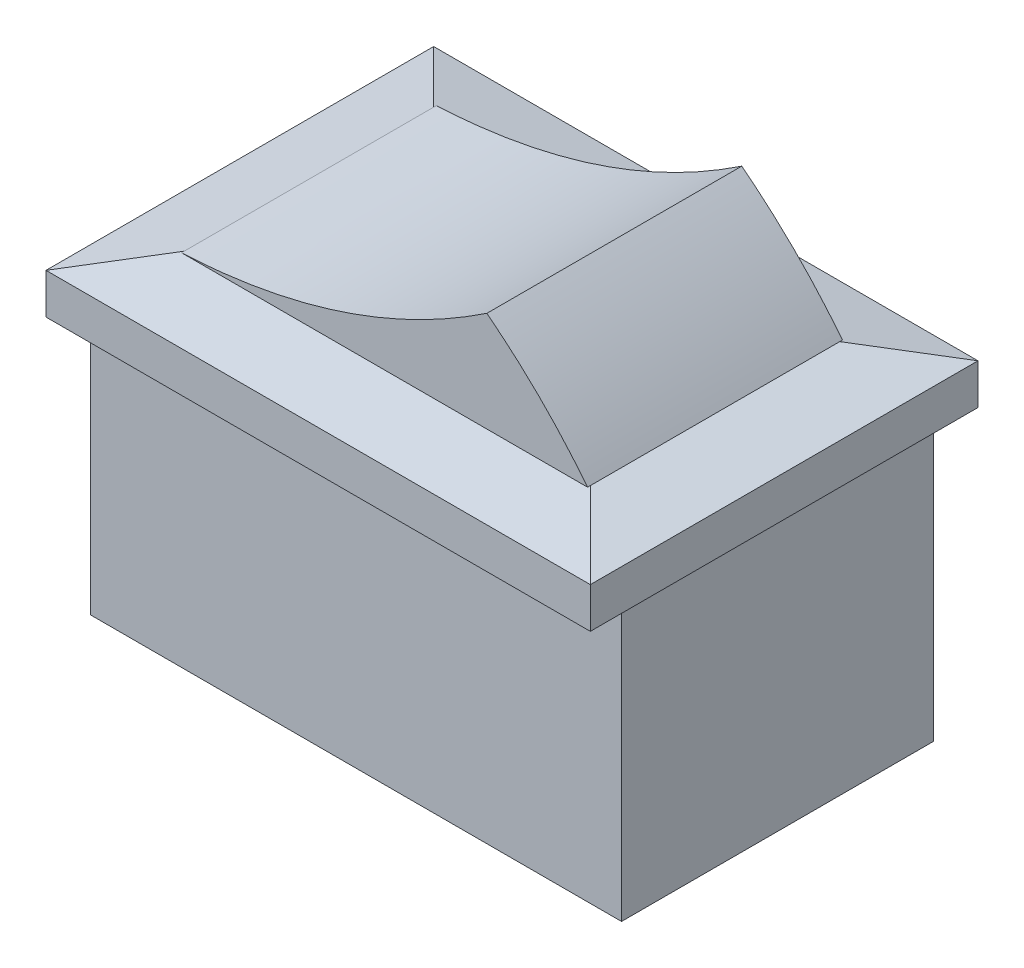
SolidWorks part; units mm, degrees
ref_plane "Front Plane" through (0, 0, 0) normal (0, 0, 1) x (1, 0, 0)
ref_plane "Top Plane" through (0, 0, 0) normal (0, 1, 0) x (1, 0, 0)
ref_plane "Right Plane" through (0, 0, 0) normal (1, 0, 0) x (0, 0, -1)
sketch "Sketch1" plane through (0, 0, 0) normal (0, 1, 0) x (1, 0, 0)
  line L1 (-10.16, 5.969) -> (10.16, 5.969)
  line L2 (-10.16, 5.969) -> (-10.16, -5.969)
  line L3 (-10.16, -5.969) -> (10.16, -5.969)
  line L4 (10.16, 5.969) -> (10.16, -5.969)
  line L5 (-10.16, 5.969) -> (10.16, -5.969) construction
  line L6 (-10.16, -5.969) -> (10.16, 5.969) construction
  point P0 (0, 0)
  dimension "D1" = 20.32
  dimension "D2" = 11.938
extrude "Boss-Extrude1" add sketch "Sketch1" against normal blind 10.4648
sketch "Sketch2" plane through (0, 0, 0) normal (0, 1, 0) x (1, 0, 0)
  line L1 (-10.414, 7.4168) -> (10.414, 7.4168)
  line L2 (-10.414, 7.4168) -> (-10.414, -7.4168)
  line L3 (-10.414, -7.4168) -> (10.414, -7.4168)
  line L4 (10.414, 7.4168) -> (10.414, -7.4168)
  line L5 (-10.414, 7.4168) -> (10.414, -7.4168) construction
  line L6 (-10.414, -7.4168) -> (10.414, 7.4168) construction
  point P0 (0, 0)
  dimension "D1" = 20.828
  dimension "D2" = 14.8336
extrude "Boss-Extrude2" add sketch "Sketch2" along normal blind 2.1844
chamfer "Chamfer1" distance 0.635 angle 76.5 4 edges at (0, 2.1844, 7.4168) (-10.414, 2.1844, 0) (0, 2.1844, -7.4168) (10.414, 2.1844, 0)
sketch "Sketch11" plane through (0, 0, 0) normal (0, 0, 1) x (1, 0, 0)
  line L0 (-7.769, 2.1844) -> (3.915, 2.1844) construction
  line L1 (-7.769, 2.1844) -> (7.769, 2.1844) construction
  line L2 (3.915, 2.1844) -> (3.915, 6.0198) construction
  line L3 (-7.769, 2.1844) -> (7.769, 2.1844)
  spline S0 degree 2 poles (-7.769, 2.1844) (-1.382, 2.4775) (3.915, 6.0198) knots 0 0 0 1 1 1
  spline S1 degree 2 poles (3.915, 6.0198) (6.0765, 4.3365) (7.769, 2.1844) knots 0 0 0 1 1 1
  point P8 (6.0473, 4.1312)
  dimension "D1" = 11.684
  dimension "D2" = 3.8354
extrude "Boss-Extrude3" add sketch "Sketch11" along normal mid plane 9.7536
